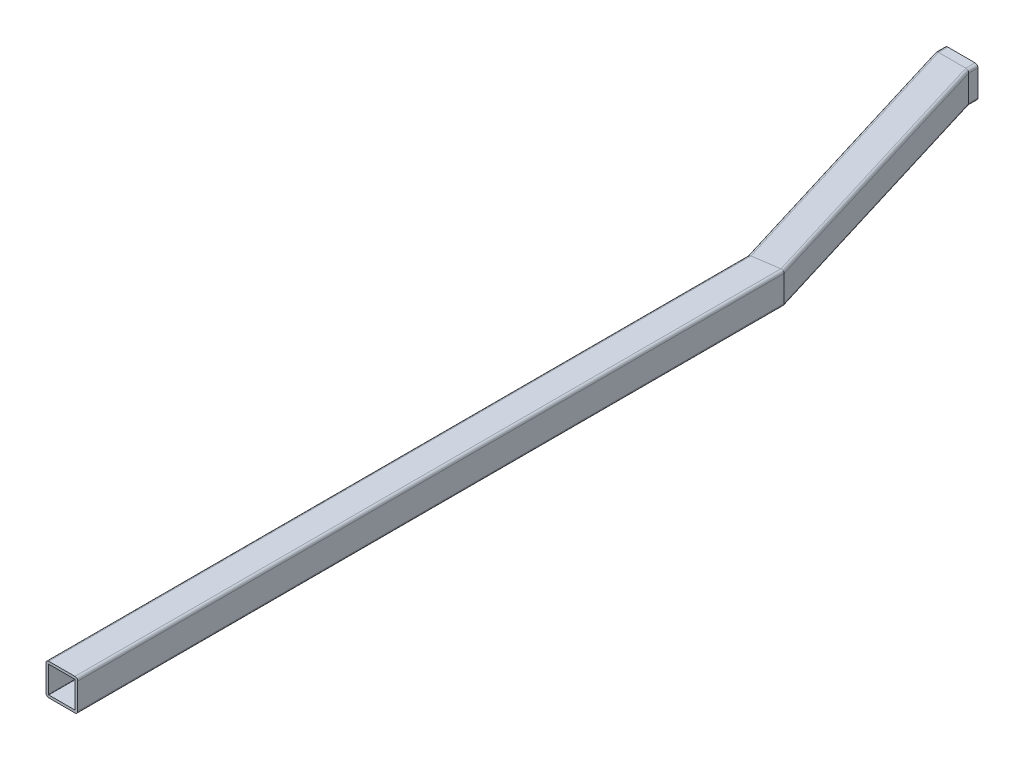
SolidWorks part; units mm, degrees
material "AISI 1020 Steel, Cold Rolled"
ref_plane "Front Plane" through (0, 0, 0) normal (0, 0, 1) x (1, 0, 0)
ref_plane "Top Plane" through (0, 0, 0) normal (0, 1, 0) x (1, 0, 0)
ref_plane "Right Plane" through (0, 0, 0) normal (1, 0, 0) x (0, 0, -1)
sketch "Sketch1" plane through (0, 0, 0) normal (0, 1, 0) x (1, 0, 0)
  line L7 (-326.7662, 255) -> (-326.7662, -300)
  line L8 (-392.4171, 470) -> (-326.7662, 255)
  point P0 (0, 0)
  dimension "D1" = 555
  dimension "D2" = 770
  dimension "D3" = 224.8
other "Structural Member1"
ref_plane "Plane1" through (-326.7662, 0, -255) normal (0, 0, 1) x (1, 0, 0)
sketch "Sketch11" plane through (-326.7662, 0, -255) normal (0, 0, 1) x (1, 0, 0)
  line L0 (-10.3, -10.5) -> (10.3, -10.5)
  line L1 (-10.5, -10.3) -> (-10.5, 10.3)
  line L2 (10.3, 10.5) -> (-10.3, 10.5)
  line L3 (10.5, 10.3) -> (10.5, -10.3)
  line L4 (-10.3, -12.5) -> (10.3, -12.5)
  line L5 (-12.5, -10.3) -> (-12.5, 10.3)
  line L6 (10.3, 12.5) -> (-10.3, 12.5)
  line L7 (12.5, 10.3) -> (12.5, -10.3)
  arc A0 (12.5, 10.3) -> (10.3, 12.5) centre (10.3, 10.3) ccw
  arc A1 (10.3, -12.5) -> (12.5, -10.3) centre (10.3, -10.3) ccw
  arc A2 (-12.5, -10.3) -> (-10.3, -12.5) centre (-10.3, -10.3) ccw
  arc A3 (-10.3, 12.5) -> (-12.5, 10.3) centre (-10.3, 10.3) ccw
  arc A4 (-10.3, 10.5) -> (-10.5, 10.3) centre (-10.3, 10.3) ccw
  arc A5 (10.5, 10.3) -> (10.3, 10.5) centre (10.3, 10.3) ccw
  arc A6 (10.3, -10.5) -> (10.5, -10.3) centre (10.3, -10.3) ccw
  arc A7 (-10.5, -10.3) -> (-10.3, -10.5) centre (-10.3, -10.3) ccw
  point P0 (-12.5, 0)
  point P1 (12.5, 0)
  point P2 (0, 12.5)
  point P3 (0, -12.5)
  point P4 (0, 0)
  point P5 (-12.5, -12.5)
  point P6 (12.5, -12.5)
  point P7 (12.5, 12.5)
  point P8 (-12.5, 12.5)
  point P33 (0, 0)
  dimension "D1" = 2.2
  dimension "Thickness" = 2
  dimension "V_leg" = 25
ref_plane "Plane2" through (0, 42.5, 0) normal (0, 1, 0) x (-1, 0, 0)
sketch "Sketch13" plane through (0, 42.5, 0) normal (0, 1, 0) x (-1, 0, 0)
  line L0 (404.3721, -466.3495) -> (378.2326, -466.3495)
  line L1 (404.3721, -466.3495) -> (380.462, -473.6505)
  line L2 (380.462, -473.6505) -> (378.2326, -466.3495)
  dimension "D1" = 7.301
  dimension "D2" = 7.301
extrude "Cut-Extrude1" cut sketch "Sketch13" against normal blind 74
sketch "Sketch14" plane through (0, 0, -466.3495) normal (0, 0, -1) x (-1, 0, 0)
  line L4 (378.2326, 10.3) -> (378.2326, -10.3)
  line L5 (380.5329, -12.5) -> (402.0718, -12.5)
  line L6 (404.3721, -10.3) -> (404.3721, 10.3)
  line L7 (402.0718, 12.5) -> (380.5329, 12.5)
  line L8 (378.2326, 10.3) -> (378.2326, -10.3)
  line L9 (380.5329, -12.5) -> (402.0718, -12.5)
  line L10 (404.3721, -10.3) -> (404.3721, 10.3)
  line L11 (402.0718, 12.5) -> (380.5329, 12.5)
  ellipse E4 centre (380.5329, -10.3) end of major axis (382.8332, -10.3) minor radius 2.2 (378.2326, -10.3) -> (380.5329, -12.5) ccw
  ellipse E5 centre (402.0718, -10.3) end of major axis (404.3721, -10.3) minor radius 2.2 (402.0718, -12.5) -> (404.3721, -10.3) ccw
  ellipse E6 centre (402.0718, 10.3) end of major axis (404.3721, 10.3) minor radius 2.2 (404.3721, 10.3) -> (402.0718, 12.5) ccw
  ellipse E7 centre (380.5329, 10.3) end of major axis (382.8332, 10.3) minor radius 2.2 (380.5329, 12.5) -> (378.2326, 10.3) ccw
  ellipse E8 centre (380.5329, -10.3) end of major axis (382.8332, -10.3) minor radius 2.2 (378.2326, -10.3) -> (380.5329, -12.5) ccw
  ellipse E9 centre (402.0718, -10.3) end of major axis (404.3721, -10.3) minor radius 2.2 (402.0718, -12.5) -> (404.3721, -10.3) ccw
  ellipse E10 centre (402.0718, 10.3) end of major axis (404.3721, 10.3) minor radius 2.2 (404.3721, 10.3) -> (402.0718, 12.5) ccw
  ellipse E11 centre (380.5329, 10.3) end of major axis (382.8332, 10.3) minor radius 2.2 (380.5329, 12.5) -> (378.2326, 10.3) ccw
  dimension "D1" = 0
extrude "Boss-Extrude1" add sketch "Sketch14" along normal blind 7.304 separate body
